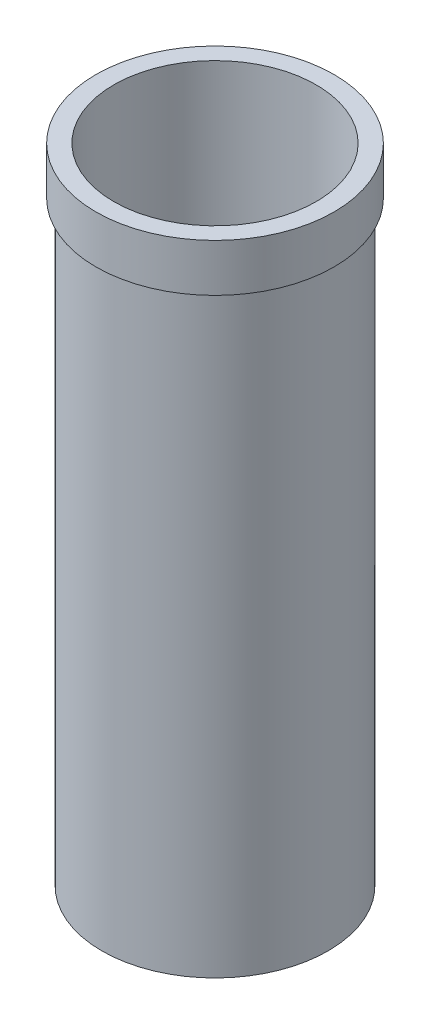
SolidWorks part; units mm, degrees
ref_plane "Front Plane" through (0, 0, 0) normal (0, 0, 1) x (1, 0, 0)
ref_plane "Top Plane" through (0, 0, 0) normal (0, 1, 0) x (1, 0, 0)
ref_plane "Right Plane" through (0, 0, 0) normal (1, 0, 0) x (0, 0, -1)
sketch "Sketch2" plane through (0, 0, 0) normal (0, 1, 0) x (1, 0, 0)
  circle A0 centre (0, 0) radius 4.25
  circle A1 centre (0, 0) radius 4.75
  dimension "D1" = 8.5
  dimension "D2" = 9.5
extrude "Boss-Extrude1" add sketch "Sketch2" along normal blind 25
sketch "Sketch3" plane through (0, 25, 0) normal (0, 1, 0) x (1, 0, 0)
  circle A0 centre (0, 0) radius 5
  circle A1 centre (0, 0) radius 4.25
  dimension "D1" = 10
  dimension "D2" = 8.5
extrude "Boss-Extrude2" add sketch "Sketch3" along normal blind 2
